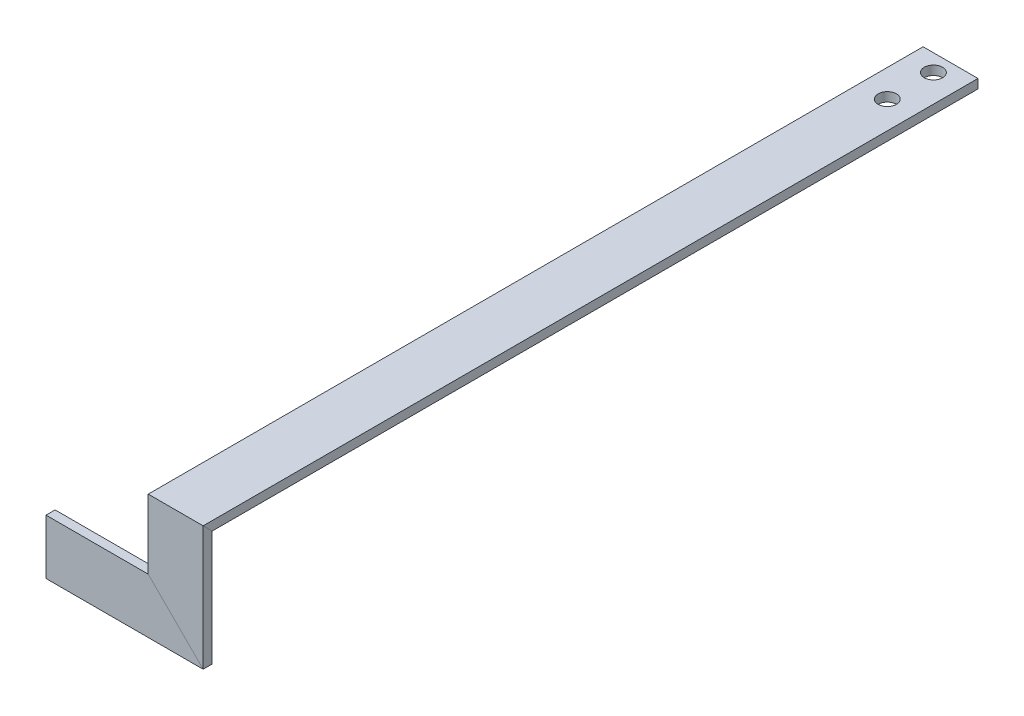
SolidWorks part; units mm, degrees
ref_plane "Alzado" through (0, 0, 0) normal (0, 0, 1) x (1, 0, 0)
ref_plane "Planta" through (0, 0, 0) normal (0, 1, 0) x (1, 0, 0)
ref_plane "Vista lateral" through (0, 0, 0) normal (1, 0, 0) x (0, 0, -1)
sketch "Croquis1" plane through (0, 0, 0) normal (0, 0, 1) x (1, 0, 0)
  line L1 (-19.05, 3.155) -> (19.05, 3.155)
  line L2 (-19.05, 3.155) -> (-19.05, -3.155)
  line L3 (-19.05, -3.155) -> (19.05, -3.155)
  line L4 (19.05, 3.155) -> (19.05, -3.155)
  line L5 (-19.05, 3.155) -> (19.05, -3.155) construction
  line L6 (-19.05, -3.155) -> (19.05, 3.155) construction
  point P0 (0, 0)
  dimension "D1" = 38.1
  dimension "D2" = 6.31
sketch3d "Croquis3D1"
  line L0 (0, 0, 0) -> (0, 0, 534.55)
  line L1 (0, 0, 534.55) -> (0, -64, 534.55)
  line L2 (0, -64, 534.55) -> (-90, -64, 534.55)
  dimension "D1" = 534.55
  dimension "D2" = 64
  dimension "D3" = 90
sweep "Barrer1" add profiles "Croquis1" path "Croquis3D1"
sketch "Croquis2" plane through (0, 3.155, 0) normal (0, 1, 0) x (1, 0, 0)
  circle A0 centre (0, -43.8922) radius 6.35
  circle A1 centre (0, -11.8922) radius 6.35
extrude "Cortar-Extruir1" cut sketch "Croquis2" against normal blind 6.31
